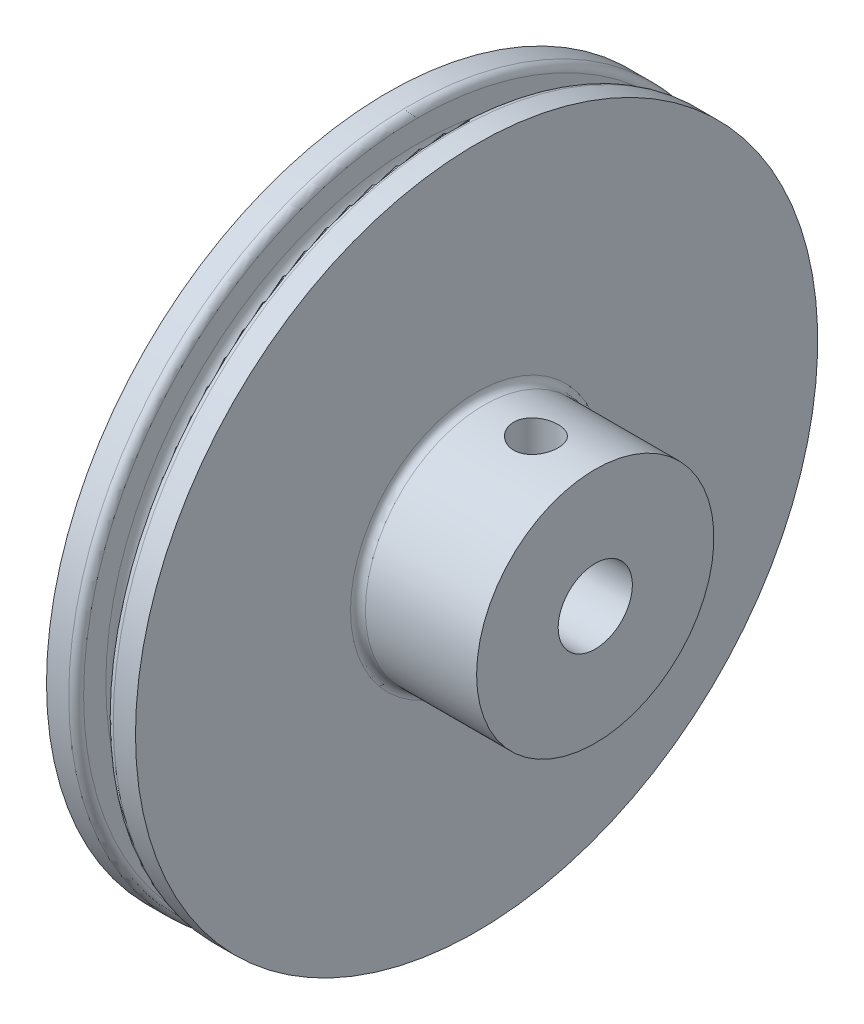
SolidWorks part; units mm, degrees
ref_plane "Front Plane" through (0, 0, 0) normal (0, 0, 1) x (1, 0, 0)
ref_plane "Top Plane" through (0, 0, 0) normal (0, 1, 0) x (1, 0, 0)
ref_plane "Right Plane" through (0, 0, 0) normal (1, 0, 0) x (0, 0, -1)
sketch "Sketch1" plane through (0, 0, 0) normal (0, 0, 1) x (1, 0, 0)
  line L0 (-11.5427, -7.9771) -> (2.4573, -7.9771) construction
  line L1 (-11.5427, 15.0229) -> (-10.0427, 15.0229)
  line L2 (-11.5427, 15.0229) -> (-11.5427, -5.4771)
  line L3 (-11.5427, -5.4771) -> (2.4573, -5.4771)
  line L4 (-5.5427, 15.0229) -> (-5.5427, 0.5229)
  line L5 (2.4573, -5.4771) -> (2.4573, 0.0229)
  line L6 (2.4573, 0.0229) -> (-5.0427, 0.0229)
  line L7 (-7.5427, 14.5229) -> (-7.5427, 13.0229)
  line L8 (-7.0427, 15.0229) -> (-5.5427, 15.0229)
  line L10 (-9.5427, 14.5229) -> (-9.5427, 13.0229)
  arc A0 (-9.5427, 13.0229) -> (-7.5427, 13.0229) centre (-8.5427, 13.0229) ccw
  arc A1 (-9.5427, 14.5229) -> (-10.0427, 15.0229) centre (-10.0427, 14.5229) ccw
  arc A2 (-7.5427, 14.5229) -> (-7.0427, 15.0229) centre (-7.0427, 14.5229) cw
  arc A3 (-5.0427, 0.0229) -> (-5.5427, 0.5229) centre (-5.0427, 0.5229) cw
  point P8 (-8.5427, 16.0229)
  point P15 (-7.5427, 15.0229)
  dimension "D1" = 0.5
  dimension "D2" = 0.5
  dimension "D4" = 0.5
  dimension "D3" = 23
  dimension "D5" = 2.5
revolve "Revolve1" add sketch "Sketch1" angle 360 about L0
sketch "Sketch7" plane through (0, 0, 0) normal (0, 1, 0) x (1, 0, 0)
  line L0 (-5.5427, 0) -> (2.4573, 0) construction
  line L1 (-5.5427, -23) -> (-5.5427, 23) construction
  line L2 (2.4573, -8) -> (2.4573, 8) construction
  circle A0 centre (-1.5427, 0) radius 1.5
extrude "Cut-Extrude3" cut sketch "Sketch7" against normal blind 8 and the other way blind 2
